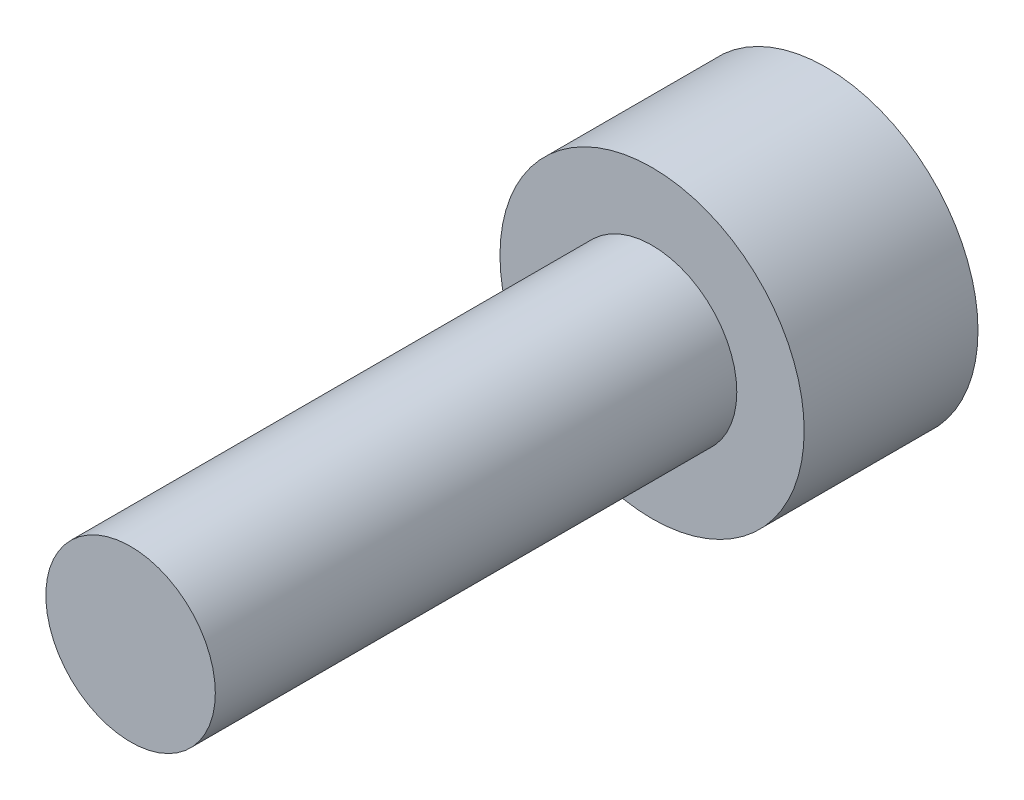
SolidWorks part; units mm, degrees
ref_plane "정면" through (0, 0, 0) normal (0, 0, 1) x (1, 0, 0)
ref_plane "윗면" through (0, 0, 0) normal (0, 1, 0) x (1, 0, 0)
ref_plane "우측면" through (0, 0, 0) normal (1, 0, 0) x (0, 0, -1)
sketch "스케치1" plane through (0, 0, 0) normal (0, 0, 1) x (1, 0, 0)
  circle A0 centre (0, 0) radius 1.95
  dimension "D1" = 3.9
extrude "보스-돌출1" add sketch "스케치1" along normal blind 12
sketch "스케치2" plane through (0, 0, 0) normal (0, 0, 1) x (1, 0, 0)
  circle A0 centre (0, 0) radius 3.5
  dimension "D1" = 7
extrude "보스-돌출2" add sketch "스케치2" against normal blind 4
